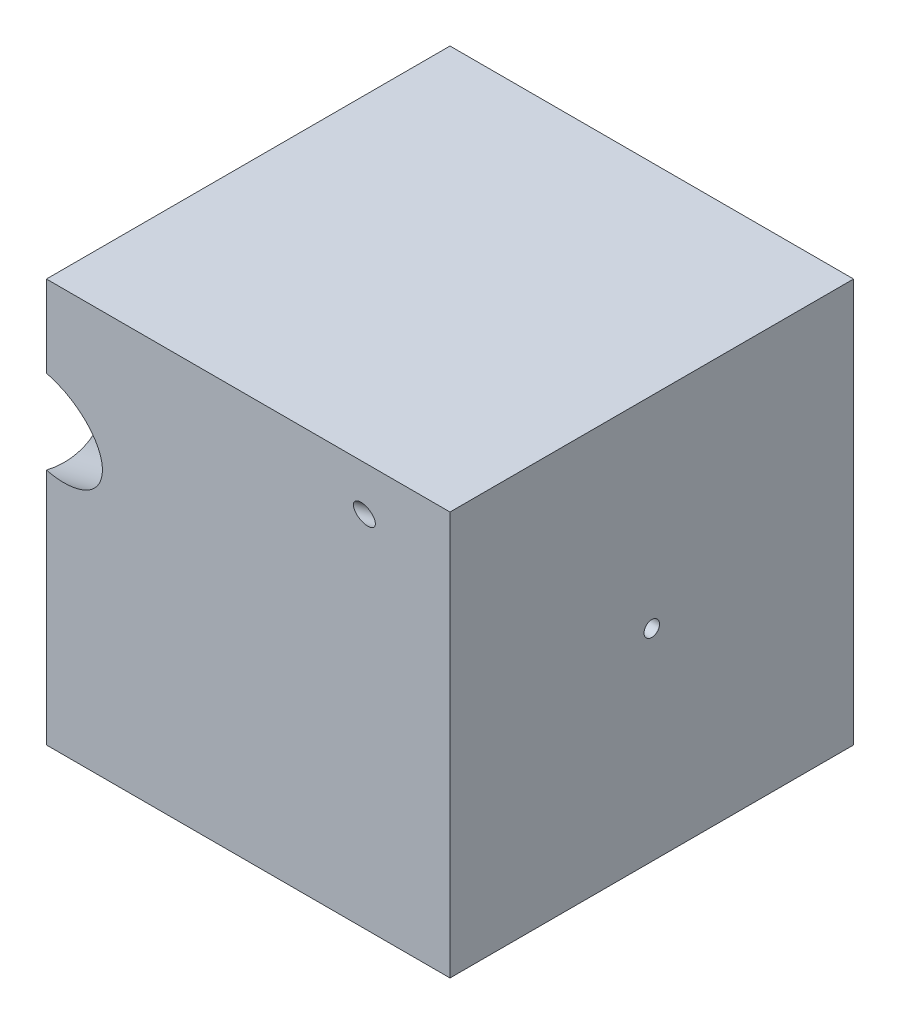
SolidWorks part; units mm, degrees
material "6061 Alloy"
ref_plane "Front Plane" through (0, 0, 0) normal (0, 0, 1) x (1, 0, 0)
ref_plane "Top Plane" through (0, 0, 0) normal (0, 1, 0) x (1, 0, 0)
ref_plane "Right Plane" through (0, 0, 0) normal (1, 0, 0) x (0, 0, -1)
sketch "Square" plane through (0, 0, 0) normal (0, 0, 1) x (1, 0, 0)
  line L1 (-26, -26) -> (26, -26)
  line L2 (-26, -26) -> (-26, 26)
  line L3 (-26, 26) -> (26, 26)
  line L4 (26, -26) -> (26, 26)
  line L5 (-26, -26) -> (26, 26) construction
  line L6 (-26, 26) -> (26, -26) construction
  point P0 (0, 0)
  dimension "D1" = 52
extrude "Cube-Extrusion" add sketch "Square" along normal blind 52
ref_plane "StickPlane" through (-28.8889, 14.4444, 28.8889) normal (0.6667, -0.3333, -0.6667) x (-0.7454, -0.2981, -0.5963)
sketch "Stick-Hole" plane through (-28.8889, 14.4444, 28.8889) normal (0.6667, -0.3333, -0.6667) x (-0.7454, -0.2981, -0.5963)
  line L0 (-19.3793, 0) -> (-3.8759, -46.5102) construction
  circle A0 centre (-14.6358, -14.2302) radius 5.1
  dimension "D2" = 10.2
  dimension "D1" = 15
extrude "Stick-Cut" cut sketch "Stick-Hole" against normal through all from offset 15
sketch "Sketch1" plane through (-28.8889, 14.4444, 28.8889) normal (0.6667, -0.3333, -0.6667) x (-0.7454, -0.2981, -0.5963)
  circle A0 centre (-48.1937, -5.1576) radius 1
  dimension "D1" = 2
extrude "Cut-Extrude1" cut sketch "Sketch1" along normal blind 24
sketch "Sketch2" plane through (-26, 0, 0) normal (-1, 0, 0) x (0, 0, 1)
  line L0 (0, 26) -> (0, -26) construction
  line L2 (52, -26) -> (0, -26) construction
  circle A0 centre (5.25, -22) radius 1
  point P6 (0, 0)
  point P8 (4.3898, -26)
  point P9 (0, 0)
  point P11 (0, 0)
  dimension "D1" = 2
  dimension "D2" = 5.25
  dimension "D3" = 4
extrude "Cut-Extrude2" cut sketch "Sketch2" against normal blind 12
ref_plane "RefPlane1" through (5.2, -10.4, 0) normal (0.4472, -0.8944, 0) x (-0.8944, -0.4472, 0)
ref_plane "Plane1_nonRef" through (-12.6885, 25.3771, 0) normal (0.4472, -0.8944, 0) x (-0.8944, -0.4472, 0)
sketch "Sketch6" plane through (-12.6885, 25.3771, 0) normal (0.4472, -0.8944, 0) x (-0.8944, -0.4472, 0)
  line L1 (11.6276, -52) -> (11.6276, 0) construction
  line L2 (11.6276, 0) -> (34.8827, 0) construction
  circle A0 centre (13.1276, -6.0621) radius 1
  point P2 (0, 0)
  point P3 (12.5229, -6.0621)
  dimension "D1" = 2
  dimension "D2" = 1.5
  dimension "D3" = 6.0621
extrude "Cut-Extrude4" cut sketch "Sketch6" against normal mid plane 12
sketch "Sketch7" plane through (26, 0, 0) normal (1, 0, 0) x (0, 0, -1)
  line L1 (-52, 26) -> (0, 26) construction
  circle A0 centre (-26, 0) radius 1
  point P2 (0, 0)
  point P3 (0, 0)
  point P6 (-26, 26)
  dimension "D1" = 2
extrude "Cut-Extrude5" cut sketch "Sketch7" against normal blind 12
sketch "Sketch8" plane through (0, 0, 0) normal (0, 0, -1) x (-1, 0, 0)
  circle A0 centre (0, 0) radius 1
  dimension "D1" = 2
extrude "Cut-Extrude6" cut sketch "Sketch8" against normal blind 12
ref_plane "Plane4Ref" through (-4.3333, -8.6667, 4.3333) normal (0.4082, 0.8165, -0.4082) x (0.9129, -0.3651, 0.1826)
ref_plane "Plane5" through (-20.6633, -41.3265, 20.6633) normal (0.4082, 0.8165, -0.4082) x (0.9129, -0.3651, 0.1826)
sketch "Sketch11" plane through (-20.6633, -41.3265, 20.6633) normal (0.4082, 0.8165, -0.4082) x (0.9129, -0.3651, 0.1826)
  line L0 (-4.7469, -34.8827) -> (42.7224, -34.8827) construction
  line L1 (-4.7469, -34.8827) -> (-14.2408, 11.6276) construction
  circle A0 centre (22.1933, -28.9124) radius 1
  point P2 (-1.1468, -28.9124)
  point P5 (0, 0)
  point P7 (0, 0)
  dimension "D1" = 2
  dimension "D2" = 5.9703
  dimension "D3" = 27.59
extrude "Cut-Extrude7" cut sketch "Sketch11" along normal blind 25
